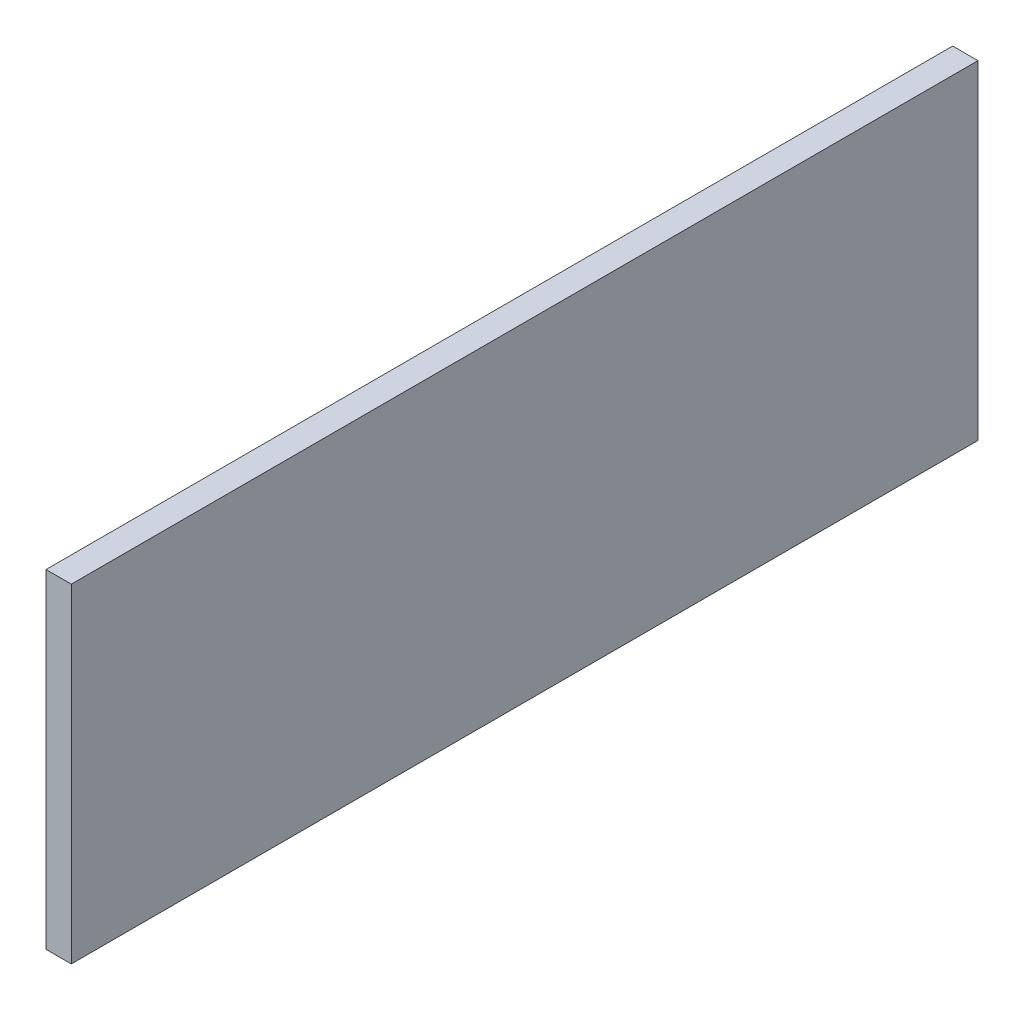
SolidWorks part; units mm, degrees
ref_plane "Front Plane" through (0, 0, 0) normal (0, 0, 1) x (1, 0, 0)
ref_plane "Top Plane" through (0, 0, 0) normal (0, 1, 0) x (1, 0, 0)
ref_plane "Right Plane" through (0, 0, 0) normal (1, 0, 0) x (0, 0, -1)
sketch "Sketch1" plane through (0, 0, 0) normal (1, 0, 0) x (0, 0, -1)
  line L1 (-63.7989, 39.3049) -> (151.2011, 39.3049)
  line L2 (-63.7989, 39.3049) -> (-63.7989, -38.6951)
  line L3 (-63.7989, -38.6951) -> (151.2011, -38.6951)
  line L4 (151.2011, 39.3049) -> (151.2011, -38.6951)
  dimension "D1" = 78
  dimension "D2" = 215
extrude "Boss-Extrude1" add sketch "Sketch1" along normal blind 6
